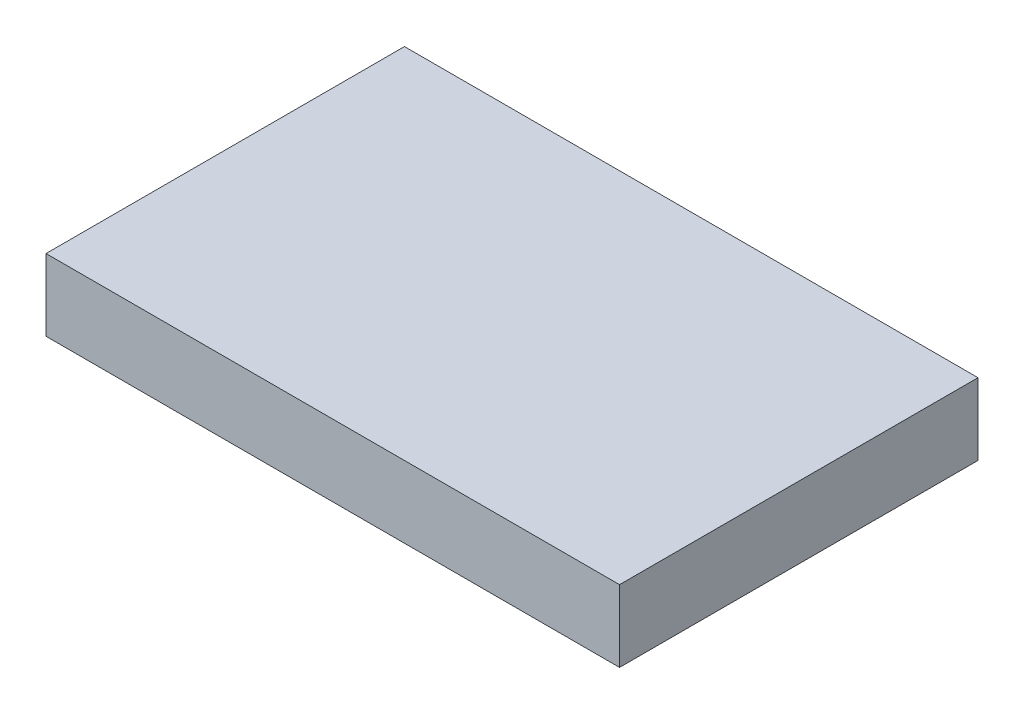
SolidWorks part; units mm, degrees
ref_plane "前视基准面" through (0, 0, 0) normal (0, 0, 1) x (1, 0, 0)
ref_plane "上视基准面" through (0, 0, 0) normal (0, 1, 0) x (1, 0, 0)
ref_plane "右视基准面" through (0, 0, 0) normal (1, 0, 0) x (0, 0, -1)
sketch "草图1" plane through (0, 0, 0) normal (0, 1, 0) x (1, 0, 0)
  line L1 (-33.1325, 18.7048) -> (6.8675, 18.7048)
  line L2 (-33.1325, 18.7048) -> (-33.1325, -6.2952)
  line L3 (-33.1325, -6.2952) -> (6.8675, -6.2952)
  line L4 (6.8675, 18.7048) -> (6.8675, -6.2952)
  line L5 (-13.1325, -6.2952) -> (-13.1325, 18.7048) construction
  line L6 (-33.1325, 6.2048) -> (6.8675, 6.2048) construction
  point P0 (-13.1325, 6.2048)
  dimension "D1" = 40
  dimension "D2" = 25
extrude "凸台-拉伸1" add sketch "草图1" along normal blind 5
